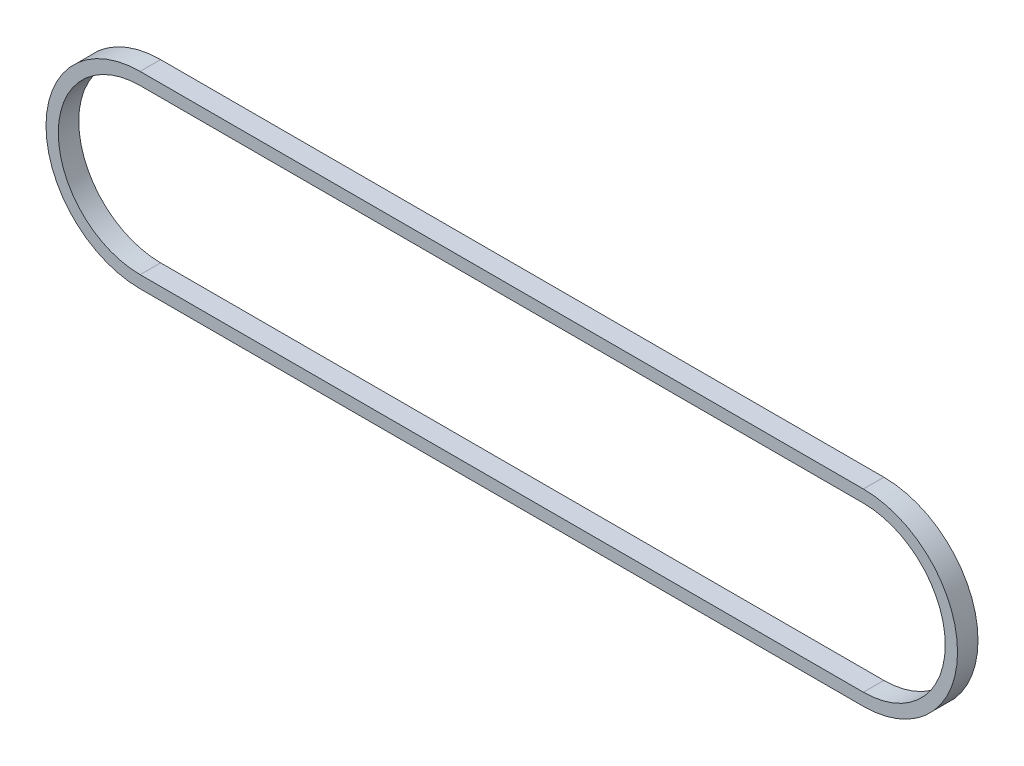
SolidWorks part; units mm, degrees
ref_plane "Front Plane" through (0, 0, 0) normal (0, 0, 1) x (1, 0, 0)
ref_plane "Top Plane" through (0, 0, 0) normal (0, 1, 0) x (1, 0, 0)
ref_plane "Right Plane" through (0, 0, 0) normal (1, 0, 0) x (0, 0, -1)
sketch "Sketch1" plane through (0, 0, 0) normal (0, 0, 1) x (1, 0, 0)
  line L0 (88.35, 0) -> (-88.35, 0) construction
  line L1 (88.35, -20) -> (-88.35, -20)
  line L2 (88.35, 20) -> (-88.35, 20)
  line L3 (88.35, -23) -> (-88.35, -23)
  line L4 (88.35, 23) -> (-88.35, 23)
  arc A0 (88.35, -20) -> (88.35, 20) centre (88.35, 0) ccw
  arc A1 (-88.35, 20) -> (-88.35, -20) centre (-88.35, 0) ccw
  arc A2 (-88.35, 23) -> (-88.35, -23) centre (-88.35, 0) ccw
  arc A3 (88.35, -23) -> (88.35, 23) centre (88.35, 0) ccw
  point P2 (0, 0)
  dimension "D2" = 20
  dimension "D1" = 176.7
  dimension "D3" = 3
extrude "Boss-Extrude1" add sketch "Sketch1" along normal mid plane 5
